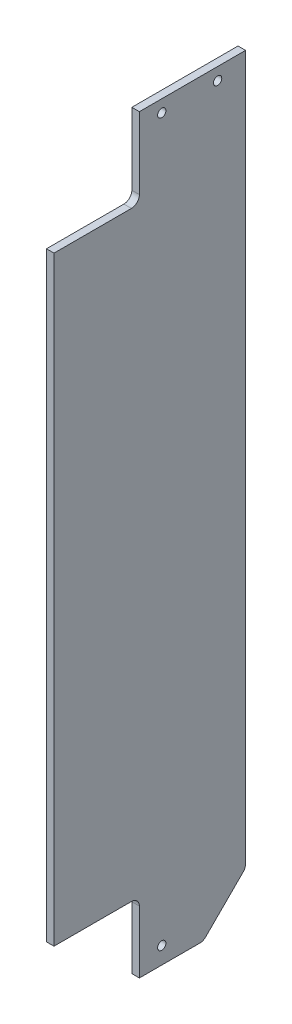
SolidWorks part; units mm, degrees
ref_plane "Front Plane" through (0, 0, 0) normal (0, 0, 1) x (1, 0, 0)
ref_plane "Top Plane" through (0, 0, 0) normal (0, 1, 0) x (1, 0, 0)
ref_plane "Right Plane" through (0, 0, 0) normal (1, 0, 0) x (0, 0, -1)
sketch "Sketch1" plane through (0, 0, 0) normal (1, 0, 0) x (0, 0, -1)
  line L0 (0, 0) -> (0, -266.7) construction
  line L1 (-15.875, 0) -> (18.0975, 0)
  line L2 (18.0975, 0) -> (18.0975, 31.75)
  line L3 (18.0975, 31.75) -> (60.325, 31.75)
  line L4 (60.325, 31.75) -> (60.325, -249.8725)
  line L5 (60.325, -249.8725) -> (43.4975, -266.7)
  line L6 (43.4975, -266.7) -> (18.0975, -266.7)
  line L7 (18.0975, -266.7) -> (18.0975, -238.76)
  line L8 (18.0975, -238.76) -> (-15.875, -238.76)
  line L9 (-15.875, -238.76) -> (-15.875, 0)
  line L10 (26.9875, 31.75) -> (26.9875, -266.7) construction
  line L11 (-15.875, -116.5416) -> (60.325, -116.5416) construction
  line L12 (26.9875, 26.8732) -> (49.2125, 26.8732) construction
  circle A0 centre (26.9875, 26.8732) radius 1.65
  circle A1 centre (49.2125, 26.8732) radius 1.65
  circle A2 centre (26.9875, -259.9563) radius 1.65
  point P20 (38.1, 26.8732)
  point P23 (-15.875, -116.5416)
  dimension "D5" = 3.3
  dimension "D6" = 286.8295
  dimension "D1" = 76.2
  dimension "D2" = 298.45
  dimension "D3" = 15.875
  dimension "D4" = 22.225
  dimension "D7" = 135
  dimension "D8" = 31.75
  dimension "D9" = 8.89
  dimension "D10" = 38.1
  dimension "D11" = 25.4
  dimension "D12" = 4.8768
  dimension "D13" = 27.94
extrude "Boss-Extrude1" add sketch "Sketch1" along normal blind 3
fillet "Fillet1" radius 3.175 4 edges at (1.5, -249.8725, -60.325) (1.5, -266.7, -43.4975) (1.5, 0, -18.0975) (1.5, -238.76, -18.0975)
